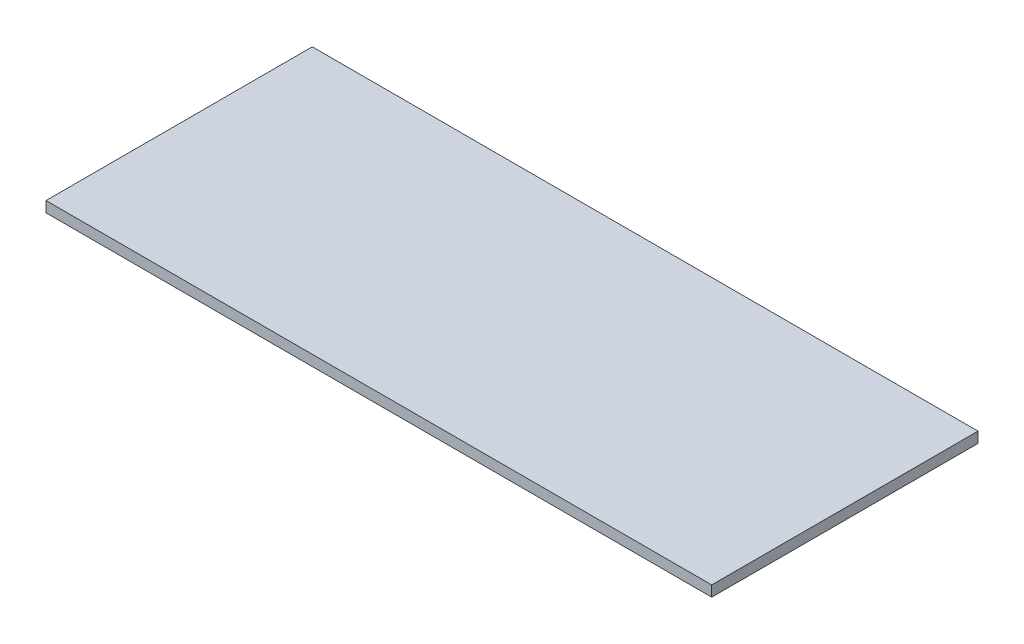
SolidWorks part; units mm, degrees
material "Бальса"
ref_plane "Спереди" through (0, 0, 0) normal (0, 0, 1) x (1, 0, 0)
ref_plane "Сверху" through (0, 0, 0) normal (0, 1, 0) x (1, 0, 0)
ref_plane "Справа" through (0, 0, 0) normal (1, 0, 0) x (0, 0, -1)
sketch "Эскиз1" plane through (0, 0, 0) normal (0, 1, 0) x (1, 0, 0)
  line L1 (0, 0) -> (1250, 0)
  line L2 (0, 0) -> (0, 500)
  line L3 (0, 500) -> (1250, 500)
  line L4 (1250, 0) -> (1250, 500)
  dimension "D1" = 1250
  dimension "D2" = 500
extrude "Бобышка-Вытянуть1" add sketch "Эскиз1" along normal blind 20
sketch "Эскиз2" [suppressed] plane through (0, 20, 0) normal (0, 1, 0) x (1, 0, 0)
  line L1 (0, 200) -> (20, 200)
  line L2 (0, 200) -> (0, 100)
  line L3 (0, 100) -> (20, 100)
  line L4 (20, 200) -> (20, 100)
  dimension "D1" = 20
  dimension "D2" = 100
extrude "Вырез-Вытянуть1" [suppressed] cut sketch "Эскиз2" against normal through all
fillet "Скругление1" [suppressed] radius 20
sketch "Эскиз3" [suppressed] plane through (0, 20, 0) normal (0, 1, 0) x (1, 0, 0)
  line L0 (50, 450) -> (50, 500) construction
  line L1 (50, 450) -> (910, 450)
  line L2 (50, 450) -> (50, 50)
  line L3 (50, 50) -> (910, 50)
  line L4 (910, 450) -> (910, 50)
  line L5 (960, 500) -> (0, 500) construction
  line L6 (0, 450) -> (50, 450) construction
  line L7 (0, 500) -> (0, 0) construction
  line L9 (910, 50) -> (960, 50) construction
  line L10 (960, 0) -> (960, 500) construction
  line L11 (910, 50) -> (910, 0) construction
  line L12 (0, 0) -> (960, 0) construction
  dimension "D1" = 50
extrude "Вырез-Вытянуть2" [suppressed] cut sketch "Эскиз3" against normal through all
sketch "Эскиз4" [suppressed] plane through (0, 20, 0) normal (0, 1, 0) x (1, 0, 0)
  line L0 (65, 950) -> (65, 750) construction
  line L1 (80, 950) -> (80, 750)
  line L2 (50, 950) -> (50, 750)
  line L3 (0, 1000) -> (0, 0) construction
  line L4 (1250, 1000) -> (0, 1000) construction
  arc A0 (80, 950) -> (50, 950) centre (65, 950) ccw
  arc A1 (50, 750) -> (80, 750) centre (65, 750) ccw
  point P2 (65, 850)
  dimension "D1" = 30
  dimension "D2" = 200
  dimension "D3" = 50
  dimension "D4" = 50
extrude "Вырез-Вытянуть3" [suppressed] cut sketch "Эскиз4" against normal through all
